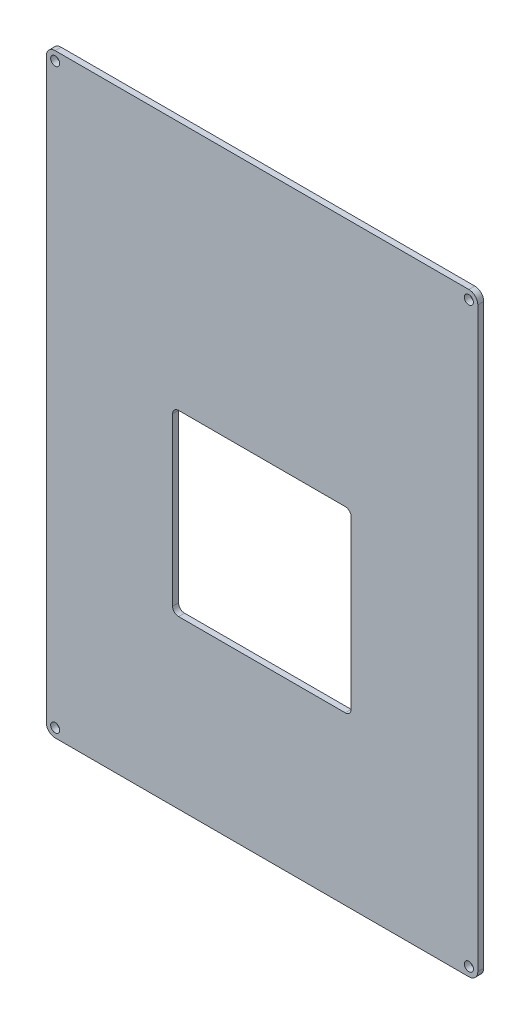
SolidWorks part; units mm, degrees
material "Verre"
ref_plane "Plan de face" through (0, 0, 0) normal (0, 0, 1) x (1, 0, 0)
ref_plane "Plan de dessus" through (0, 0, 0) normal (0, 1, 0) x (1, 0, 0)
ref_plane "Plan de droite" through (0, 0, 0) normal (1, 0, 0) x (0, 0, -1)
sketch "Esquisse1" plane through (0, 0, 0) normal (0, 0, 1) x (1, 0, 0)
  line L1 (-69.5, -97.5) -> (69.5, -97.5)
  line L2 (-72.5, -94.5) -> (-72.5, 99.5)
  line L3 (-69.5, 102.5) -> (69.5, 102.5)
  line L4 (72.5, -94.5) -> (72.5, 99.5)
  line L5 (-72.5, -97.5) -> (72.5, 102.5) construction
  line L6 (-72.5, 102.5) -> (72.5, -97.5) construction
  arc A0 (-69.5, -97.5) -> (-72.5, -94.5) centre (-69.5, -94.5) cw
  arc A1 (69.5, -97.5) -> (72.5, -94.5) centre (69.5, -94.5) ccw
  arc A2 (69.5, 102.5) -> (72.5, 99.5) centre (69.5, 99.5) cw
  arc A3 (-72.5, 99.5) -> (-69.5, 102.5) centre (-69.5, 99.5) cw
  point P0 (0, 2.5)
  dimension "D3" = 3
  dimension "D1" = 145
  dimension "D2" = 200
extrude "Boss.-Extru.1" add sketch "Esquisse1" along normal blind 2
sketch "Esquisse2" plane through (0, 0, 0) normal (0, 0, -1) x (-1, 0, 0)
  line L0 (-15.9142, 5.6203) -> (15.9142, -26.2081) construction
  line L2 (-27.9456, -41.4495) -> (28.0544, -41.4495)
  line L3 (-29.9456, -39.4495) -> (-29.9456, 16.5505)
  line L4 (-27.9456, 18.5505) -> (28.0544, 18.5505)
  line L5 (30.0544, -39.4495) -> (30.0544, 16.5505)
  line L6 (-29.9456, -41.4495) -> (30.0544, 18.5505) construction
  line L7 (-29.9456, 18.5505) -> (30.0544, -41.4495) construction
  arc A0 (-27.9456, -41.4495) -> (-29.9456, -39.4495) centre (-27.9456, -39.4495) cw
  arc A1 (28.0544, -41.4495) -> (30.0544, -39.4495) centre (28.0544, -39.4495) ccw
  arc A2 (28.0544, 18.5505) -> (30.0544, 16.5505) centre (28.0544, 16.5505) cw
  arc A3 (-29.9456, 16.5505) -> (-27.9456, 18.5505) centre (-27.9456, 16.5505) cw
  point P2 (0.0544, -11.4495)
  dimension "D2" = 2
  dimension "D1" = 60
  dimension "60" = 60
extrude "Enlèv. mat.-Extru.1" cut sketch "Esquisse2" against normal blind 10
sketch "Esquisse3" plane through (0, 0, 2) normal (0, 0, 1) x (1, 0, 0)
  circle A0 centre (69.5, 99.5) radius 1.52
  circle A1 centre (-69.5, 99.5) radius 1.52
  circle A2 centre (-69.5, -94.5) radius 1.52
  circle A3 centre (69.5, -94.5) radius 1.52
extrude "Enlèv. mat.-Extru.2" cut sketch "Esquisse3" against normal blind 10
